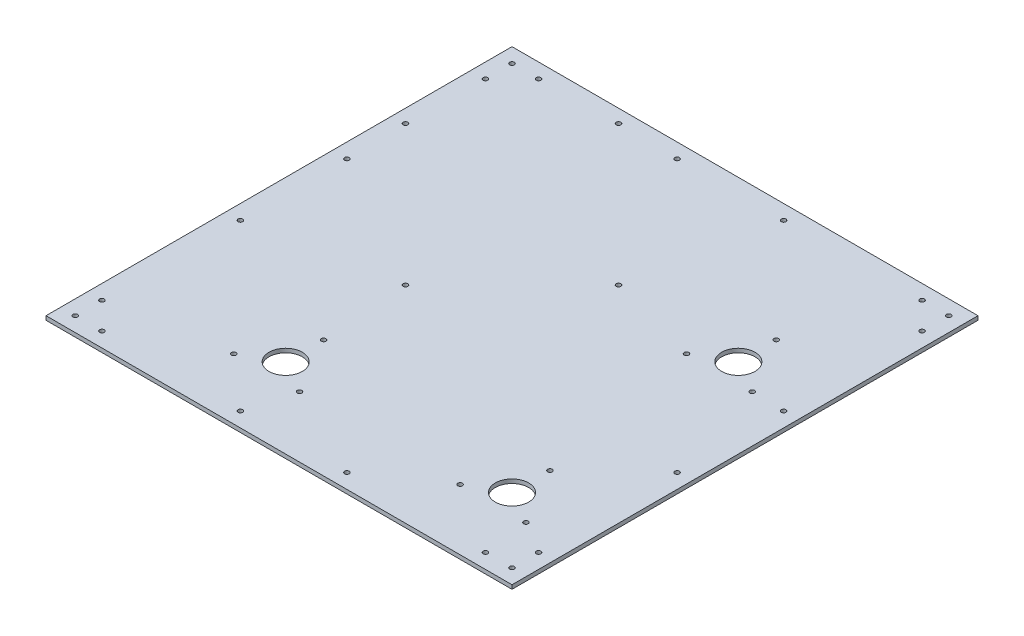
SolidWorks part; units mm, degrees
ref_plane "前视基准面" through (0, 0, 0) normal (0, 0, 1) x (1, 0, 0)
ref_plane "上视基准面" through (0, 0, 0) normal (0, 1, 0) x (1, 0, 0)
ref_plane "右视基准面" through (0, 0, 0) normal (1, 0, 0) x (0, 0, -1)
sketch "草图1" plane through (0, 0, 0) normal (0, 1, 0) x (1, 0, 0)
  line L1 (-175, -175) -> (175, -175)
  line L2 (-175, -175) -> (-175, 175)
  line L3 (-175, 175) -> (175, 175)
  line L4 (175, -175) -> (175, 175)
  line L5 (-175, -175) -> (175, 175) construction
  line L6 (-175, 175) -> (175, -175) construction
  point P0 (0, 0)
  dimension "D1" = 350
  dimension "D2" = 350
extrude "板" add sketch "草图1" along normal blind 3 contours L2 L3 L4 L1
sketch "草图2" plane through (0, 3, 0) normal (0, 1, 0) x (1, 0, 0)
  line L0 (-175, 175) -> (175, -175) construction
  line L1 (165, -165) -> (-165, -165) construction
  line L2 (165, -165) -> (165, 165) construction
  line L3 (165, 165) -> (-165, 165) construction
  line L4 (-165, -165) -> (-165, 165) construction
  line L5 (165, -165) -> (-165, 165) construction
  line L6 (165, 165) -> (-165, -165) construction
  line L7 (-175, -175) -> (-175, 175) construction
  line L8 (-175, 175) -> (175, 175) construction
  line L9 (-175, -175) -> (175, 175) construction
  line L10 (-85, 165) -> (20.061, 59.939) construction
  line L11 (-85, 165) -> (-165, 85) construction
  line L28 (-165, 85) -> (-59.939, -20.061) construction
  line L29 (20.061, 59.939) -> (-59.939, -20.061) construction
  line L30 (-55, -115) -> (115, -115) construction
  line L35 (115, -115) -> (115, 55) construction
  circle A4 centre (20.061, 59.939) radius 1.75
  circle A6 centre (-59.939, -20.061) radius 1.75
  circle A7 centre (-165, 85) radius 1.75
  circle A9 centre (-85, 165) radius 1.75
  circle A10 centre (-55, -115) radius 12.5
  circle A11 centre (-55, -115) radius 28.5 construction
  circle A12 centre (115, -115) radius 12.5
  circle A13 centre (115, -115) radius 28.5 construction
  circle A14 centre (115, 55) radius 12.5
  circle A15 centre (115, 55) radius 28.5 construction
  circle A18 centre (-55, -86.5) radius 1.75
  circle A19 centre (115, -86.5) radius 1.75
  circle A22 centre (115, 83.5) radius 1.75
  circle A25 centre (139.6817, 40.75) radius 1.75
  circle A26 centre (90.3183, 40.75) radius 1.75
  circle A27 centre (-30.3183, -129.25) radius 1.75
  circle A28 centre (-79.6817, -129.25) radius 1.75
  circle A29 centre (139.6817, -129.25) radius 1.75
  circle A30 centre (90.3183, -129.25) radius 1.75
  point P35 (115, 55)
  point P42 (-55, -115)
  point P50 (115, -115)
  dimension "D2" = 3.5
  dimension "D6" = 170
  dimension "D7" = 57
  dimension "D8" = 25
  dimension "D12" = 3.5
  dimension "D1" = 10
  dimension "D3" = 90
  dimension "D4" = 50
  dimension "D5" = 148.5786
  dimension "D9" = 3
  dimension "D10" = 3
  dimension "D11" = 3
extrude "切除-拉伸1" cut sketch "草图2" against normal through all both and the other way through all
sketch "草图3" plane through (0, 3, 0) normal (0, 1, 0) x (1, 0, 0)
  line L0 (-164, 144) -> (-164, 164) construction
  line L1 (-175, 175) -> (175, -175) construction
  line L2 (-164, 164) -> (-144, 164) construction
  line L3 (-175, -175) -> (-175, 175) construction
  line L4 (-164, 40) -> (-164, -40) construction
  circle A0 centre (-164, 144) radius 1.75
  circle A1 centre (-164, 164) radius 1.75
  circle A2 centre (-144, 164) radius 1.75
  circle A3 centre (164, 164) radius 1.75
  circle A4 centre (144, 164) radius 1.75
  circle A5 centre (164, 144) radius 1.75
  circle A6 centre (164, -164) radius 1.75
  circle A7 centre (164, -144) radius 1.75
  circle A8 centre (144, -164) radius 1.75
  circle A9 centre (-164, -164) radius 1.75
  circle A10 centre (-144, -164) radius 1.75
  circle A11 centre (-164, -144) radius 1.75
  circle A12 centre (-164, 40) radius 1.75
  circle A13 centre (-164, -40) radius 1.75
  circle A14 centre (40, 164) radius 1.75
  circle A15 centre (-40, 164) radius 1.75
  circle A16 centre (164, -40) radius 1.75
  circle A17 centre (164, 40) radius 1.75
  circle A18 centre (-40, -164) radius 1.75
  circle A19 centre (40, -164) radius 1.75
  point P31 (0, 0)
  point P34 (-164, 0)
  dimension "D2" = 3.5
  dimension "D1" = 20
  dimension "D3" = 11
  dimension "D5" = 80
  dimension "D4" = 4
extrude "PVC安装" cut sketch "草图3" against normal through all
